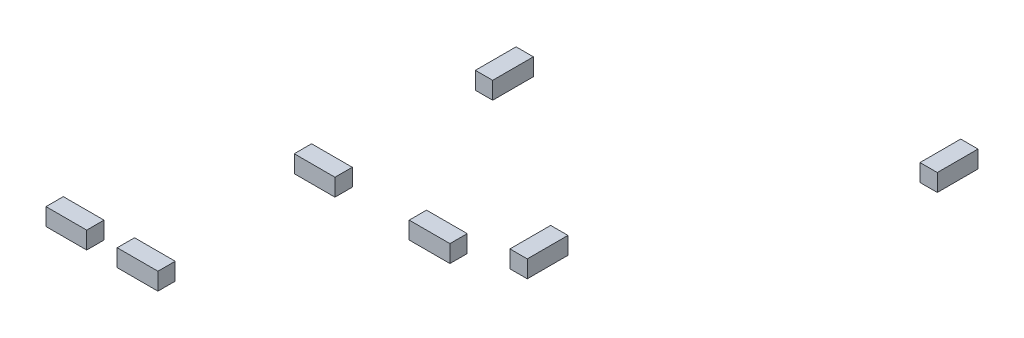
SolidWorks part; units mm, degrees
ref_plane "Front Plane" through (0, 0, 0) normal (0, 0, 1) x (1, 0, 0)
ref_plane "Top Plane" through (0, 0, 0) normal (0, 1, 0) x (1, 0, 0)
ref_plane "Right Plane" through (0, 0, 0) normal (1, 0, 0) x (0, 0, -1)
sketch "Sketch1" plane through (0, 0, 0) normal (0, 1, 0) x (1, 0, 0)
  line L0 (-0.508, 14.732) -> (-0.0762, 14.732) construction
  line L1 (-1.143, 6.35) -> (-0.127, 6.35)
  line L2 (-1.143, 6.35) -> (-1.143, 5.9182)
  line L3 (-1.143, 5.9182) -> (-0.127, 5.9182)
  line L4 (-0.127, 6.35) -> (-0.127, 5.9182)
  line L5 (-0.0762, 14.224) -> (-0.508, 14.224)
  line L6 (-0.0762, 14.224) -> (-0.0762, 15.24)
  line L7 (-0.0762, 15.24) -> (-0.508, 15.24)
  line L8 (-0.508, 14.224) -> (-0.508, 15.24)
  line L9 (7.4676, 17.78) -> (7.0358, 17.78)
  line L10 (7.4676, 17.78) -> (7.4676, 18.796)
  line L11 (7.4676, 18.796) -> (7.0358, 18.796)
  line L12 (7.0358, 17.78) -> (7.0358, 18.796)
  line L13 (-2.921, 6.35) -> (-1.905, 6.35)
  line L14 (-2.921, 6.35) -> (-2.921, 5.9182)
  line L15 (-2.921, 5.9182) -> (-1.905, 5.9182)
  line L16 (-1.905, 6.35) -> (-1.905, 5.9182)
  line L17 (-0.9652, 10.5918) -> (0.0508, 10.5918)
  line L18 (-0.9652, 10.5918) -> (-0.9652, 10.16)
  line L19 (-0.9652, 10.16) -> (0.0508, 10.16)
  line L20 (0.0508, 10.5918) -> (0.0508, 10.16)
  line L21 (1.905, 10.5918) -> (2.921, 10.5918)
  line L22 (1.905, 10.5918) -> (1.905, 10.16)
  line L23 (1.905, 10.16) -> (2.921, 10.16)
  line L24 (2.921, 10.5918) -> (2.921, 10.16)
  line L25 (3.7846, 10.795) -> (4.2164, 10.795)
  line L26 (3.7846, 10.795) -> (3.7846, 11.811)
  line L27 (3.7846, 11.811) -> (4.2164, 11.811)
  line L28 (4.2164, 10.795) -> (4.2164, 11.811)
  line L29 (7.0358, 18.288) -> (7.4676, 18.288) construction
  line L30 (4.2164, 11.303) -> (3.7846, 11.303) construction
  line L31 (-0.4572, 10.5918) -> (-0.4572, 10.16) construction
  line L32 (2.413, 10.5918) -> (2.413, 10.16) construction
  line L33 (-0.635, 6.35) -> (-0.635, 5.9182) construction
  line L34 (-2.413, 6.35) -> (-2.413, 5.9182) construction
  line L35 (-2.921, 6.1341) -> (-1.905, 6.1341) construction
  line L37 (-1.143, 6.1341) -> (-0.127, 6.1341) construction
  line L38 (-0.9652, 10.3759) -> (0.0508, 10.3759) construction
  line L39 (-10.16, -25.4) -> (10.16, -25.4) construction
  line L40 (-10.16, -25.4) -> (-10.16, 25.4) construction
  line L41 (-10.16, 25.4) -> (10.16, 25.4) construction
  line L42 (10.16, -25.4) -> (10.16, 25.4) construction
  line L43 (1.905, 10.3759) -> (2.921, 10.3759) construction
  line L44 (4.0005, 10.795) -> (4.0005, 11.811) construction
  line L45 (7.2517, 18.796) -> (7.2517, 17.78) construction
  line L46 (-0.2921, 15.24) -> (-0.2921, 14.224) construction
  point P1 (0, -25.4)
  point P2 (-10.16, 0)
  point P3 (-2.921, 6.1341)
  point P49 (-2.413, 5.9182)
  point P51 (-0.635, 5.9182)
  point P52 (-0.4572, 10.16)
  point P53 (2.413, 10.16)
  point P54 (3.7846, 11.303)
  point P55 (-0.508, 14.732)
  point P56 (7.4676, 18.288)
  point P71 (-0.2921, 14.732)
  point P72 (-0.2921, 14.732)
  point P73 (7.2517, 18.288)
  point P74 (4.0005, 11.303)
  point P75 (2.413, 10.3759)
  point P76 (-2.413, 6.1341)
  point P78 (-0.635, 6.1341)
  dimension "D2" = 0.4318
  dimension "D3" = 1.016
  dimension "D4" = 31.75
  dimension "D5" = 13.081
  dimension "D6" = 2.794
  dimension "D7" = 40.64
  dimension "D8" = 10.668
  dimension "D9" = 3.1242
  dimension "D10" = 20.32
  dimension "D11" = 50.8
  dimension "D12" = 7.62
  dimension "D13" = 3.8862
  dimension "D14" = 10.2108
  dimension "D15" = 15.24
  dimension "D16" = 14.3764
  dimension "D17" = 1.651
extrude "Boss-Extrude1" add sketch "Sketch1" along normal blind 0.4318
